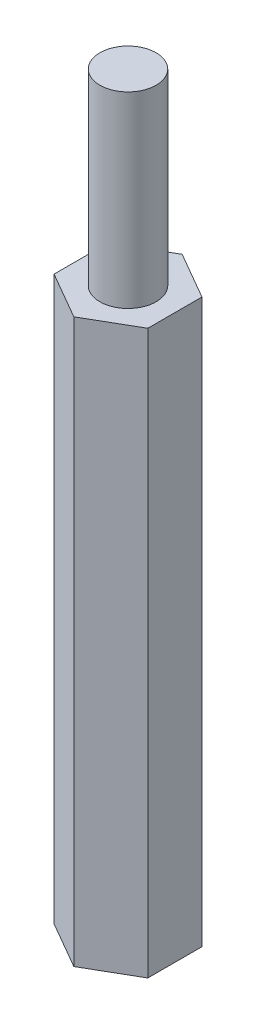
SolidWorks part; units mm, degrees
ref_plane "Front Plane" through (0, 0, 0) normal (0, 0, 1) x (1, 0, 0)
ref_plane "Top Plane" through (0, 0, 0) normal (0, 1, 0) x (1, 0, 0)
ref_plane "Right Plane" through (0, 0, 0) normal (1, 0, 0) x (0, 0, -1)
sketch "Sketch1" plane through (0, 0, 0) normal (0, 1, 0) x (1, 0, 0)
  line L1 (2.5, -1.4434) -> (2.5, 1.4434)
  line L2 (2.5, 1.4434) -> (0, 2.8868)
  line L3 (0, 2.8868) -> (-2.5, 1.4434)
  line L4 (-2.5, 1.4434) -> (-2.5, -1.4434)
  line L5 (-2.5, -1.4434) -> (0, -2.8868)
  line L6 (0, -2.8868) -> (2.5, -1.4434)
  circle A0 centre (0, 0) radius 2.5 construction
  dimension "D1" = 5
extrude "Boss-Extrude1" add sketch "Sketch1" along normal blind 30
sketch "Sketch2" plane through (0, 30, 0) normal (0, 1, 0) x (1, 0, 0)
  circle A0 centre (0, 0) radius 1.5
  dimension "D1" = 3
extrude "Boss-Extrude2" add sketch "Sketch2" along normal blind 10
sketch "Sketch3" plane through (0, 0, 0) normal (0, -1, 0) x (1, 0, 0)
  circle A0 centre (0, 0) radius 1.5
  dimension "D1" = 3
extrude "Cut-Extrude1" cut sketch "Sketch3" against normal blind 10
